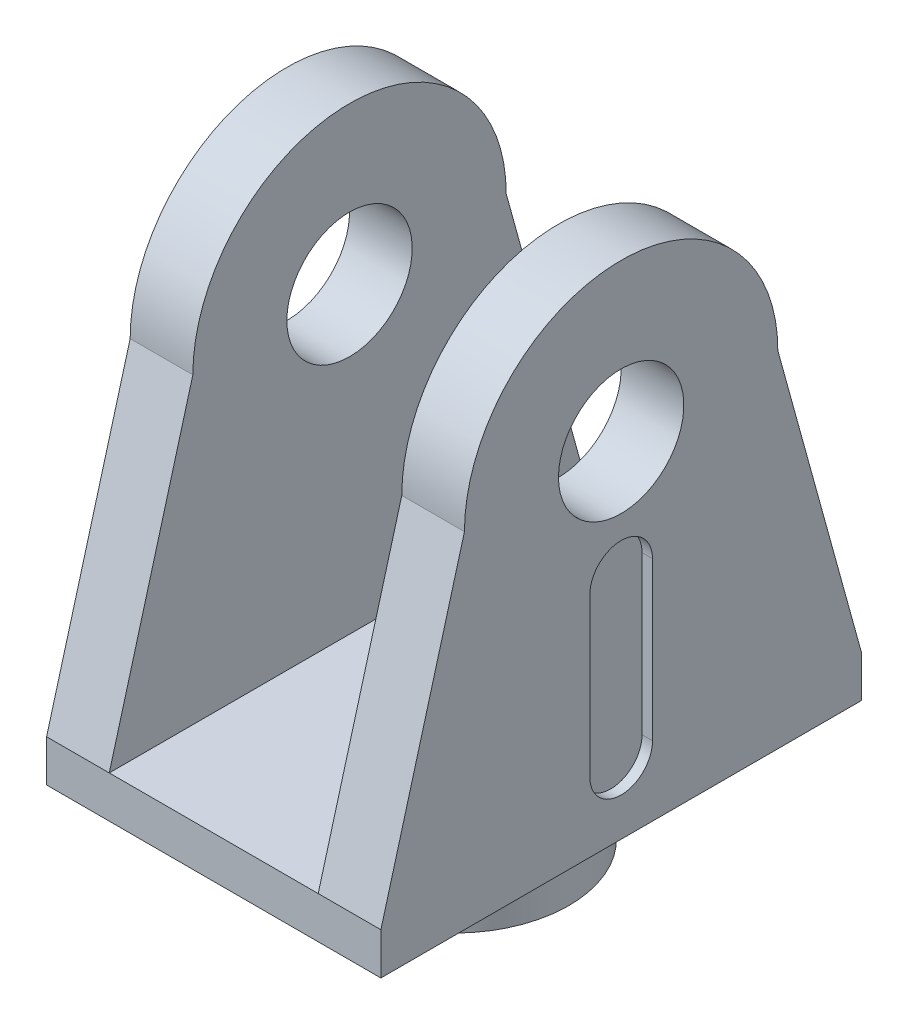
SolidWorks part; units mm, degrees
material "AISI 1020"
ref_plane "Front Plane" through (0, 0, 0) normal (0, 0, 1) x (1, 0, 0)
ref_plane "Top Plane" through (0, 0, 0) normal (0, 1, 0) x (1, 0, 0)
ref_plane "Right Plane" through (0, 0, 0) normal (1, 0, 0) x (0, 0, -1)
sketch "Sketch1" plane through (0, 0, 0) normal (0, 0, 1) x (1, 0, 0)
  line L0 (80, 0) -> (-80, 0)
  line L1 (-80, 0) -> (-80, 240)
  line L2 (-80, 240) -> (-50, 240)
  line L3 (-50, 240) -> (-50, 20)
  line L4 (-50, 20) -> (50, 20)
  line L5 (0, -55) -> (0, 55) construction
  line L6 (80, 240) -> (50, 240)
  line L7 (80, 0) -> (80, 240)
  line L8 (50, 240) -> (50, 20)
  point P12 (0, 0)
  point P13 (0, 20)
  dimension "D1" = 80
  dimension "D2" = 240
  dimension "D3" = 20
  dimension "D4" = 30
extrude "Boss-Extrude1" add sketch "Sketch1" along normal mid plane 230
sketch "Sketch2" plane through (-80, 0, 0) normal (-1, 0, 0) x (0, 0, 1)
  line L0 (115, 240) -> (-115, 240) construction
  line L1 (115, 20) -> (-115, 20) construction
  line L2 (115, 240) -> (115, 0) construction
  line L3 (-115, 240) -> (-115, 0) construction
  line L4 (115, 0) -> (-115, 0) construction
  line L5 (75, 165) -> (115, 20)
  line L6 (-75, 165) -> (-115, 20)
  circle A0 centre (0, 165) radius 30
  arc A1 (75, 165) -> (-75, 165) centre (0, 165) ccw
  line M5 (-115, 240) -> (-115, 0)
  line M7 (115, 0) -> (115, 240)
  line M8 (115, 240) -> (-115, 240)
  dimension "D1" = 60
  dimension "D2" = 150
  dimension "D3" = 165
  dimension "D4" = 20
sketch "Sketch3" plane through (0, 0, 0) normal (0, -1, 0) x (1, 0, 0)
  circle A0 centre (0, 0) radius 55
  dimension "D1" = 110
extrude "Boss-Extrude2" add sketch "Sketch3" along normal blind 40
extrude "Cut-Extrude2" cut sketch "Sketch2" against normal up to surface (160 mm away) contours A1 L6 M8 M5 | A1 L5 M7 M8 | A0 up to face at (80, 120, 0)
sketch "Sketch4" plane through (-80, 0, 0) normal (-1, 0, 0) x (0, 0, 1)
  line L0 (0, 108.8328) -> (0, 33.3522) construction
  line L1 (15, 108.8328) -> (15, 33.3522)
  line L2 (-15, 108.8328) -> (-15, 33.3522)
  line L3 (115, 0) -> (-115, 0) construction
  arc A0 (15, 108.8328) -> (-15, 108.8328) centre (0, 108.8328) ccw
  arc A1 (-15, 33.3522) -> (15, 33.3522) centre (0, 33.3522) ccw
  point P3 (0, 71.0925)
  dimension "D1" = 15
  dimension "D2" = 75.4807
  dimension "D3" = 33.3522
extrude "Cut-Extrude3" cut sketch "Sketch4" against normal blind 5
mirror "Mirror1" about plane through (0, 0, 0) normal (1, 0, 0) of "Cut-Extrude3"
